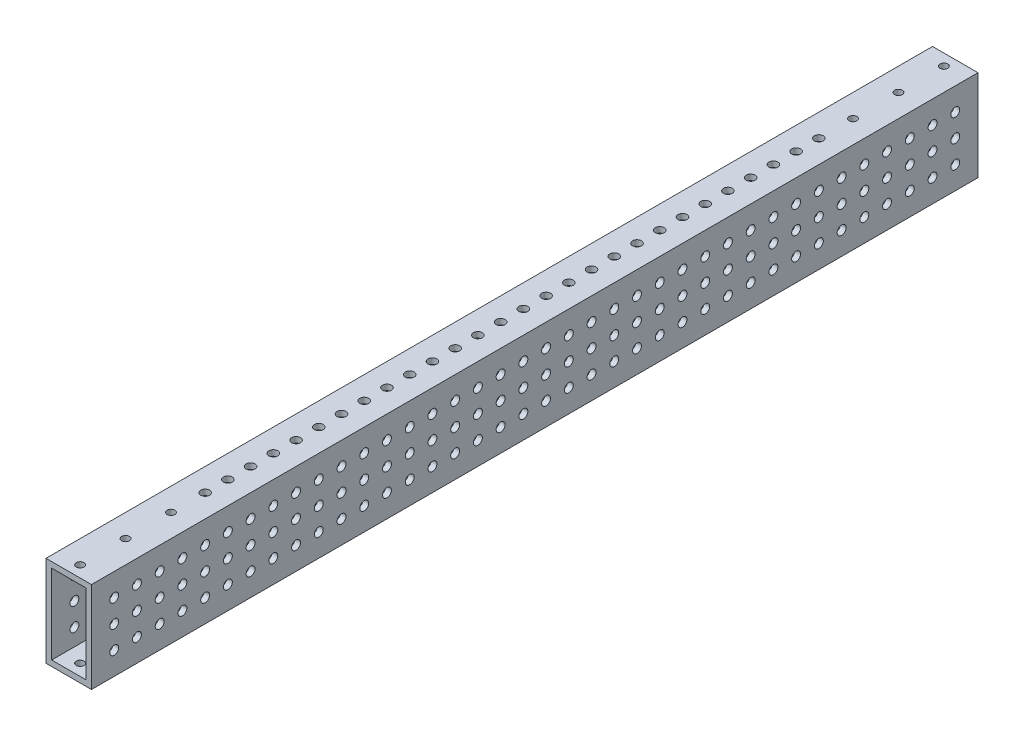
SolidWorks part; units mm, degrees
material "6061-T6 (SS)"
ref_plane "Front Plane" through (0, 0, 0) normal (0, 0, 1) x (1, 0, 0)
ref_plane "Top Plane" through (0, 0, 0) normal (0, 1, 0) x (1, 0, 0)
ref_plane "Right Plane" through (0, 0, 0) normal (1, 0, 0) x (0, 0, -1)
sketch "Sketch1" plane through (0, 0, 0) normal (0, 0, 1) x (1, 0, 0)
  line L0 (3.175, 3.175) -> (3.175, 47.625)
  line L1 (0, 0) -> (25.4, 0)
  line L2 (0, 0) -> (0, 50.8)
  line L3 (0, 50.8) -> (25.4, 50.8)
  line L4 (25.4, 0) -> (25.4, 50.8)
  line L5 (3.175, 47.625) -> (22.225, 47.625)
  line L6 (22.225, 3.175) -> (22.225, 47.625)
  line L7 (3.175, 3.175) -> (22.225, 3.175)
  dimension "D2" = 50.8
  dimension "D3" = 25.4
  dimension "D1" = 3.175
extrude "Boss-Extrude1" add sketch "Sketch1" along normal mid plane 495.3
sketch "Sketch2" plane through (0, 0, 0) normal (-1, 0, 0) x (0, 0, 1)
  line L0 (-234.95, 50.8) -> (-234.95, 0) construction
  line L1 (247.65, 50.8) -> (-247.65, 50.8) construction
  line L2 (247.65, 0) -> (-247.65, 0) construction
  line L3 (-247.65, 50.8) -> (-247.65, 0) construction
  circle A0 centre (-234.95, 38.1) radius 2.4892
  circle A1 centre (-234.95, 25.4) radius 2.4892
  circle A2 centre (-234.95, 12.7) radius 2.4892
  dimension "D1" = 4.9784
  dimension "D2" = 12.7
  dimension "D3" = 12.7
  dimension "D4" = 12.7
  dimension "D5" = 12.7
extrude "Cut-Extrude1" cut sketch "Sketch2" against normal through all
pattern_linear "LPattern1" count 38 spacing 12.7 along (0, 0, 1) of "Cut-Extrude1"
sketch "Sketch3" plane through (0, 50.8, 0) normal (0, 1, 0) x (1, 0, 0)
  line L0 (12.7, 247.65) -> (12.7, -247.65) construction
  line L1 (25.4, 247.65) -> (0, 247.65) construction
  line L2 (25.4, -247.65) -> (0, -247.65) construction
  line L3 (25.4, 0) -> (0, 0) construction
  line L4 (25.4, -247.65) -> (25.4, 247.65) construction
  line L5 (0, -247.65) -> (0, 247.65) construction
  circle A0 centre (12.7, 234.95) radius 2.4892 construction
  circle A1 centre (12.7, 222.25) radius 2.4892 construction
  circle A2 centre (12.7, 209.55) radius 2.4892 construction
  circle A3 centre (12.7, 196.85) radius 2.4892 construction
  circle A4 centre (12.7, 184.15) radius 2.4892 construction
  circle A5 centre (12.7, 171.45) radius 2.4892
  circle A6 centre (12.7, 158.75) radius 2.4892
  circle A7 centre (12.7, 146.05) radius 2.4892
  circle A8 centre (12.7, 133.35) radius 2.4892
  circle A9 centre (12.7, 120.65) radius 2.4892
  circle A10 centre (12.7, 107.95) radius 2.4892
  circle A11 centre (12.7, 95.25) radius 2.4892
  circle A12 centre (12.7, 82.55) radius 2.4892
  circle A13 centre (12.7, 69.85) radius 2.4892
  circle A14 centre (12.7, 57.15) radius 2.4892
  circle A15 centre (12.7, 44.45) radius 2.4892
  circle A16 centre (12.7, 31.75) radius 2.4892
  circle A17 centre (12.7, 19.05) radius 2.4892
  circle A18 centre (12.7, 6.35) radius 2.4892
  circle A19 centre (12.7, -6.35) radius 2.4892
  circle A20 centre (12.7, -19.05) radius 2.4892
  circle A21 centre (12.7, -31.75) radius 2.4892
  circle A22 centre (12.7, -44.45) radius 2.4892
  circle A23 centre (12.7, -57.15) radius 2.4892
  circle A24 centre (12.7, -69.85) radius 2.4892
  circle A25 centre (12.7, -82.55) radius 2.4892
  circle A26 centre (12.7, -95.25) radius 2.4892
  circle A27 centre (12.7, -107.95) radius 2.4892
  circle A28 centre (12.7, -120.65) radius 2.4892
  circle A29 centre (12.7, -133.35) radius 2.4892
  circle A30 centre (12.7, -146.05) radius 2.4892
  circle A31 centre (12.7, -158.75) radius 2.4892
  circle A32 centre (12.7, -171.45) radius 2.4892
  circle A33 centre (12.7, -184.15) radius 2.4892 construction
  circle A34 centre (12.7, -196.85) radius 2.4892 construction
  circle A35 centre (12.7, -209.55) radius 2.4892 construction
  circle A36 centre (12.7, -222.25) radius 2.4892 construction
  circle A37 centre (12.7, -234.95) radius 2.4892 construction
  circle A38 centre (12.7, 241.3) radius 2.1526
  circle A40 centre (12.7, 215.9) radius 2.1526
  circle A41 centre (12.7, 190.5) radius 2.1526
  circle A42 centre (12.7, -241.3) radius 2.1526
  circle A43 centre (12.7, -215.9) radius 2.1526
  circle A44 centre (12.7, -190.5) radius 2.1526
  dimension "D1" = 4.9784
  dimension "D5" = 4.3053
  dimension "D2" = 12.7
  dimension "D4" = 12.7
  dimension "D6" = 6.35
  dimension "D8" = 25.4
  dimension "D3" = 38
  dimension "D7" = 3
extrude "Cut-Extrude2" cut sketch "Sketch3" against normal through all
hole_wizard "1/4-20 Tapped Hole1" positions "3DSketch1" profile "Sketch4" tap size "1/4-20" standard "ANSI Inch"
sketch3d "3DSketch1"
  line L0 (12.7, 0, -146.05) -> (12.7, 3.175, -146.05) construction
  line L1 (12.7, 0, 146.05) -> (12.7, 3.175, 146.05) construction
  line L2 (12.7, 0, -19.05) -> (12.7, 3.175, -19.05) construction
  line L3 (12.7, 0, 19.05) -> (12.7, 3.175, 19.05) construction
  point P0 (12.7, 0, -146.05)
  point P4 (12.7, 0, 146.05)
  point P8 (12.7, 0, -19.05)
  point P12 (12.7, 0, 19.05)
cosmetic thread "Hole Thread1" parameters "D1"=3.302, "D2"=6.35
cosmetic thread "Hole Thread2" parameters "D1"=3.302, "D2"=6.35
cosmetic thread "Hole Thread3" parameters "D1"=3.302, "D2"=6.35
cosmetic thread "Hole Thread4" parameters "D1"=3.302, "D2"=6.35
sketch "Sketch4" plane through (12.7, 0, -146.05) normal (1, 0, 0) x (0, 0, -1)
  line L0 (0, 0) -> (0, 4.7088)
  line L1 (0, 4.7088) -> (2.5527, 3.175)
  line L2 (2.5527, 3.175) -> (2.5527, 0)
  line L5 (2.5527, 0) -> (0, 0)
  line L10 (0, 4.7088) -> (-2.5527, 3.175) construction
  line L11 (0, -6.35) -> (0, 107.95) construction
  dimension "Tap Drill Dia." = 5.1054
  dimension "Tap Drill Depth" = 3.175
  dimension "Drill Angle" = 118
